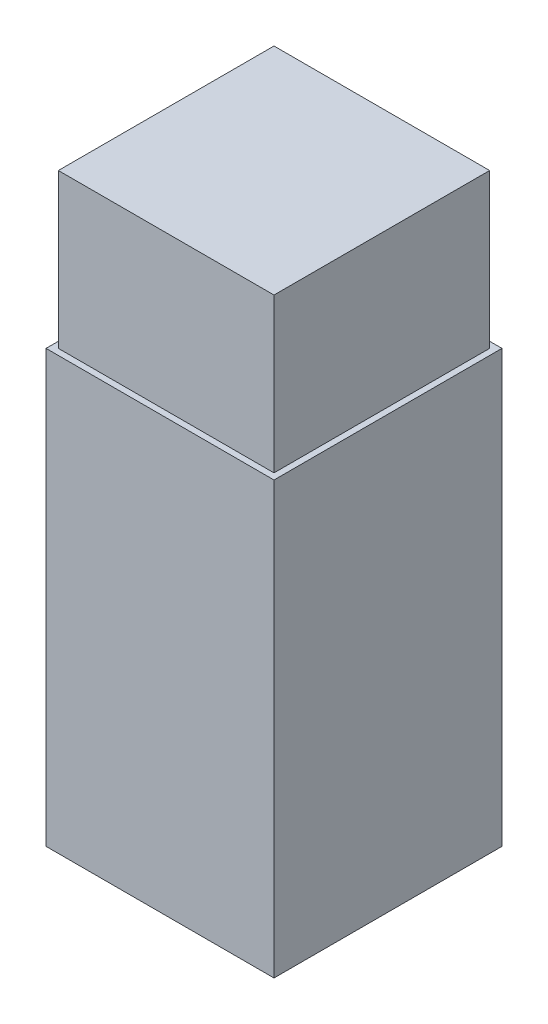
SolidWorks part; units mm, degrees
ref_plane "Front Plane" through (0, 0, 0) normal (0, 0, 1) x (1, 0, 0)
ref_plane "Top Plane" through (0, 0, 0) normal (0, 1, 0) x (1, 0, 0)
ref_plane "Right Plane" through (0, 0, 0) normal (1, 0, 0) x (0, 0, -1)
sketch "Sketch1" plane through (0, 0, 0) normal (0, 1, 0) x (1, 0, 0)
  line L1 (0, 0) -> (37, 0)
  line L2 (0, 0) -> (0, 37)
  line L3 (0, 37) -> (37, 37)
  line L4 (37, 0) -> (37, 37)
  dimension "D1" = 37
  dimension "D2" = 37
extrude "Boss-Extrude1" add sketch "Sketch1" along normal blind 70
sketch "Sketch2" plane through (0, 70, 0) normal (0, 1, 0) x (1, 0, 0)
  line L0 (37, 37) -> (0, 37) construction
  line L1 (1, 1) -> (36, 1)
  line L2 (1, 1) -> (1, 36)
  line L3 (1, 36) -> (36, 36)
  line L4 (36, 1) -> (36, 36)
  line L5 (37, 0) -> (37, 37) construction
  line L6 (0, 0) -> (37, 0) construction
  line L7 (0, 37) -> (0, 0) construction
  dimension "D1" = 1
  dimension "D2" = 1
  dimension "D3" = 1
  dimension "D4" = 1
extrude "Boss-Extrude2" add sketch "Sketch2" along normal blind 25
